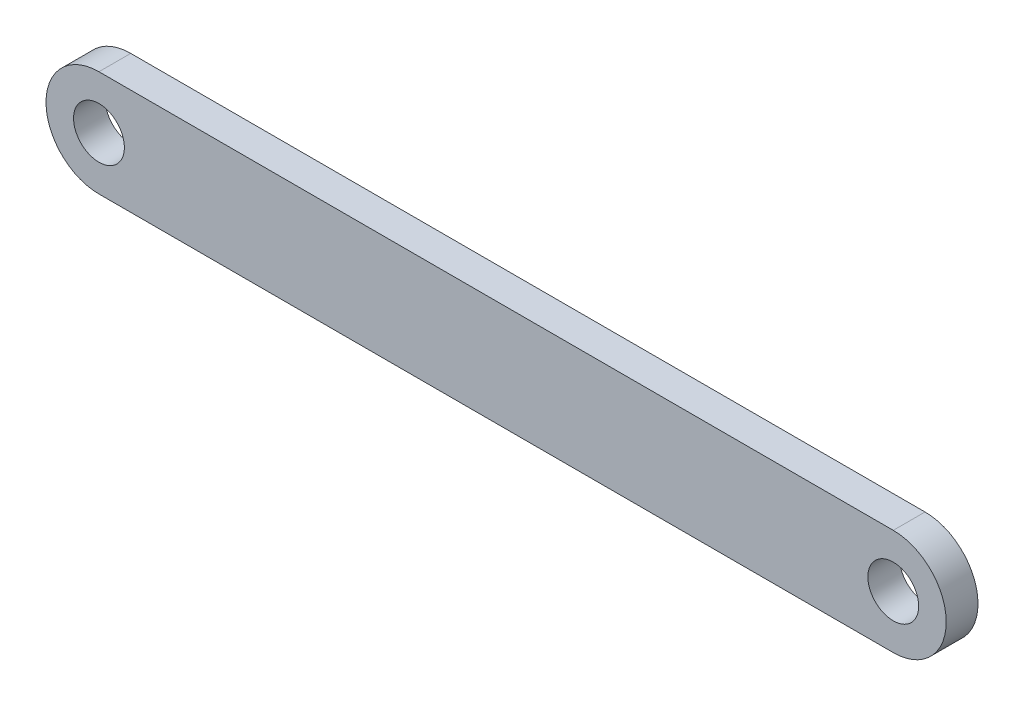
SolidWorks part; units mm, degrees
ref_plane "Front Plane" through (0, 0, 0) normal (0, 0, 1) x (1, 0, 0)
ref_plane "Top Plane" through (0, 0, 0) normal (0, 1, 0) x (1, 0, 0)
ref_plane "Right Plane" through (0, 0, 0) normal (1, 0, 0) x (0, 0, -1)
sketch "Sketch1" plane through (0, 0, 0) normal (0, 0, 1) x (1, 0, 0)
  line L1 (120.0787, 190.0323) -> (195.0787, 190.0323)
  line L3 (120.0787, 200.0323) -> (195.0787, 200.0323)
  arc A0 (120.0787, 200.0323) -> (120.0787, 190.0323) centre (120.0787, 195.0323) ccw
  arc A1 (195.0787, 200.0323) -> (195.0787, 190.0323) centre (195.0787, 195.0323) cw
  circle A2 centre (120.0787, 195.0323) radius 2.4
  circle A3 centre (195.0787, 195.0323) radius 2.4
  dimension "D3" = 4.8
  dimension "D4" = 4.8
  dimension "D1" = 75
  dimension "D2" = 10
extrude "Boss-Extrude1" add sketch "Sketch1" along normal blind 3
